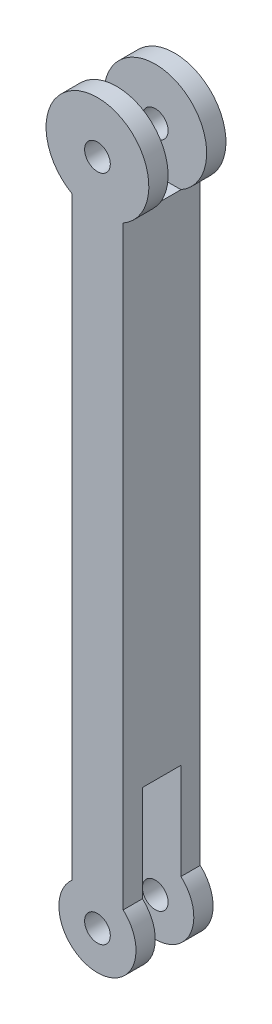
SolidWorks part; units mm, degrees
ref_plane "Alzado" through (0, 0, 0) normal (0, 0, 1) x (1, 0, 0)
ref_plane "Planta" through (0, 0, 0) normal (0, 1, 0) x (1, 0, 0)
ref_plane "Vista lateral" through (0, 0, 0) normal (1, 0, 0) x (0, 0, -1)
sketch "Croquis1" plane through (0, 0, 0) normal (0, 0, 1) x (1, 0, 0)
  line L0 (0, 0) -> (0, 54.3465) construction
  line L1 (0, 0) -> (-46.0645, 0) construction
  line L2 (-4, 46.2998) -> (-4, -46.2998)
  line L3 (0, 0) -> (0, -56.772) construction
  line L4 (4, 46.2998) -> (4, -46.2998)
  arc A0 (-4, 46.2998) -> (4, 46.2998) centre (0, 53.228) cw
  arc A1 (-4, -46.2998) -> (4, -46.2998) centre (0, -50.772) ccw
  point P3 (3.5, 0)
  point P8 (-4, 0)
  point P15 (-3.5, 0)
  dimension "D1" = 8
  dimension "D2" = 4
  dimension "D3" = 6
  dimension "D4" = 104
extrude "Saliente-Extruir1" add sketch "Croquis1" along normal blind 12
sketch "Croquis3" plane through (0, 0, 12) normal (0, 0, 1) x (1, 0, 0)
  line L0 (0, 61.228) -> (0, -56.772) construction
  arc A0 (4, 46.2998) -> (-4, 46.2998) centre (0, 53.228) ccw construction
  arc A1 (-4, -46.2998) -> (4, -46.2998) centre (0, -50.772) ccw construction
  circle A2 centre (0, 53.228) radius 2
  circle A3 centre (0, -50.772) radius 2
  dimension "D1" = 4
  dimension "D3" = 4
  dimension "D4" = 6
extrude "Cortar-Extruir1" cut sketch "Croquis3" against normal through all
ref_plane "Plano1" through (0, -46.2998, 0) normal (0, 1, 0) x (1, 0, 0)
sketch "Croquis4" plane through (0, -46.2998, 0) normal (0, 1, 0) x (1, 0, 0)
  line L0 (-6, -6) -> (6, -6) construction
  line L1 (-6, 0) -> (-6, -12) construction
  line L2 (6, -12) -> (6, 0) construction
  line L4 (15, -9) -> (-15, -9)
  line L5 (15, -9) -> (15, -3)
  line L6 (15, -3) -> (-15, -3)
  line L7 (-15, -9) -> (-15, -3)
  line L8 (15, -9) -> (-15, -3) construction
  line L9 (15, -3) -> (-15, -9) construction
  point P6 (0, -6)
  dimension "D1" = 6
  dimension "D2" = 30
extrude "Cortar-Extruir2" cut sketch "Croquis4" against normal blind 14
sketch "Croquis5" plane through (0, -46.2998, 0) normal (0, -1, 0) x (1, 0, 0)
  line L1 (-4, 9) -> (4, 9)
  line L2 (-4, 9) -> (-4, 3)
  line L3 (-4, 3) -> (4, 3)
  line L4 (4, 9) -> (4, 3)
extrude "Cortar-Extruir3" cut sketch "Croquis5" against normal blind 15
ref_plane "Plano2" through (0, 46.2998, 0) normal (0, 1, 0) x (1, 0, 0)
sketch "Croquis7" plane through (0, -46.2998, 0) normal (0, 1, 0) x (1, 0, 0)
  line L0 (-8, -6) -> (8, -6) construction
  line L1 (-8, 0) -> (-8, -12) construction
  line L2 (8, -12) -> (8, 0) construction
sketch "Croquis8" plane through (0, 46.2998, 0) normal (0, 1, 0) x (1, 0, 0)
  line L0 (-8, -6) -> (8, -6) construction
  line L1 (15, -3) -> (-15, -3)
  line L2 (15, -3) -> (15, -9)
  line L3 (15, -9) -> (-15, -9)
  line L4 (-15, -3) -> (-15, -9)
  line L5 (15, -3) -> (-15, -9) construction
  line L6 (15, -9) -> (-15, -3) construction
  point P0 (0, -6)
  dimension "D1" = 30
  dimension "D2" = 6
extrude "Cortar-Extruir6" cut sketch "Croquis8" along normal blind 39
